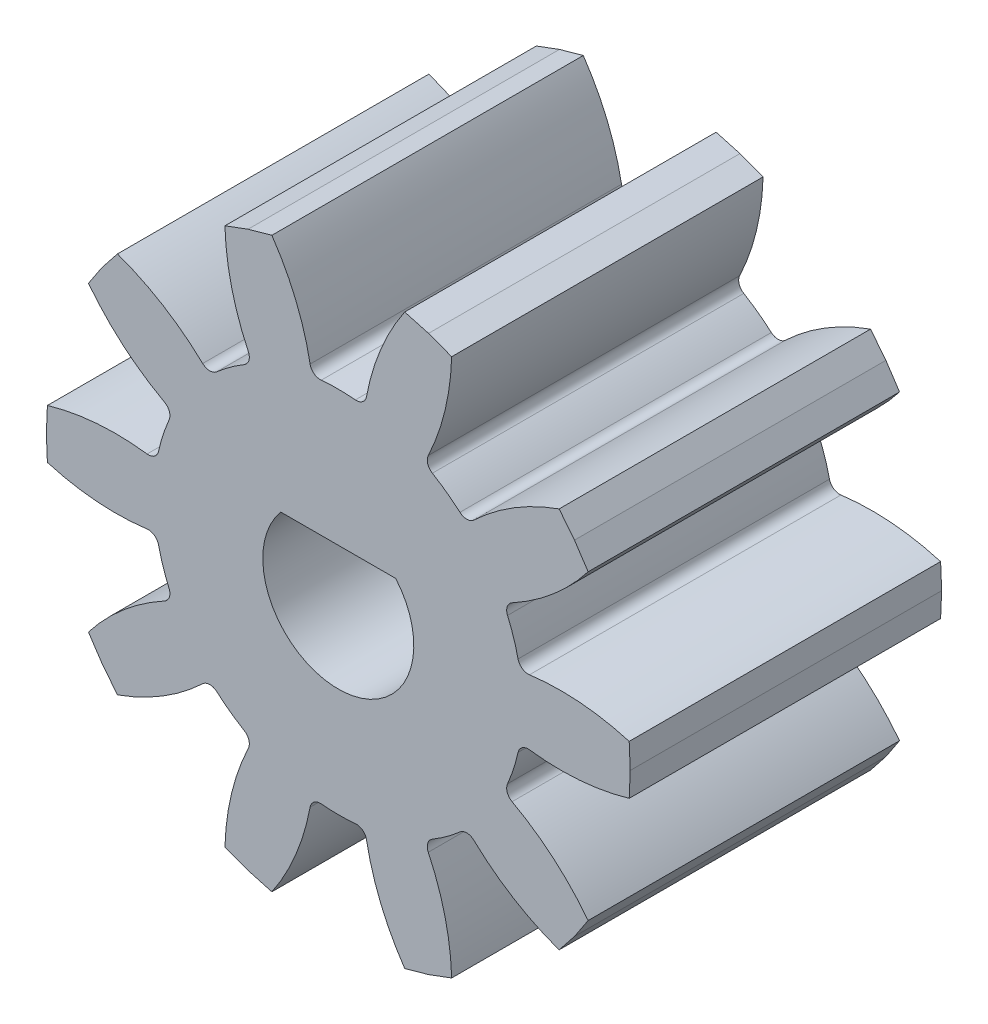
SolidWorks part; units mm, degrees
ref_plane "Front Plane" through (0, 0, 0) normal (0, 0, 1) x (1, 0, 0)
ref_plane "Top Plane" through (0, 0, 0) normal (0, 1, 0) x (1, 0, 0)
ref_plane "Right Plane" through (0, 0, 0) normal (1, 0, 0) x (0, 0, -1)
sketch "Sketch1" plane through (0, 0, 0) normal (0, 0, 1) x (1, 0, 0)
  line L0 (0, 0) -> (74.4139, 0) construction
  line L1 (0, 0) -> (5.6279, 1.8286) construction
  line L2 (0, 0) -> (74.4139, 12.7198) construction
  line L3 (0, 0) -> (74.4139, 6.3141) construction
  line L4 (9.3414, 0.7926) -> (9.375, 0)
  line L5 (0, 0) -> (5.6279, -1.8286) construction
  line L6 (0, 0) -> (5.6279, 1.8286)
  line L7 (0, 0) -> (5.6279, -1.8286) construction
  line L8 (0, 0) -> (5.6279, -1.8286)
  line L9 (9.3414, -0.7926) -> (9.375, 0)
  circle A0 centre (0, 0) radius 9.375 construction
  circle A1 centre (0, 0) radius 7.8125 construction
  circle A2 centre (0, 0) radius 5.9175 construction
  arc A3 (5.8329, 0.997) -> (9.3414, 0.7926) centre (7.1457, -6.6831) cw
  arc A4 (5.8329, 0.997) -> (5.6279, 1.8286) centre (0, 0) ccw
  arc A5 (5.8329, -0.997) -> (5.6279, -1.8286) centre (0, 0) cw
  arc A6 (5.8329, -0.997) -> (9.3414, -0.7926) centre (7.1457, 6.6831) ccw
  dimension "D1" = 18.75
  dimension "D2" = 1.5625
  dimension "D3" = 1.895
  dimension "D4" = 18
  dimension "D5" = 9.7
  dimension "D6" = 4.85
extrude "Boss-Extrude1" add sketch "Sketch1" along normal blind 10
fillet "Fillet1" radius 0.3325 2 edges at (5.8329, 0.997, 5) (5.8329, -0.997, 5)
pattern_circular "CirPattern1" count 10 over 360 about axis through (0, 0, 0) along (0, 0, 1) of "Boss-Extrude1", "Fillet1"
sketch "Sketch2" plane through (0, 0, 0) normal (0, 0, -1) x (-1, 0, 0)
  line L0 (-1.8439, 1.575) -> (1.8439, 1.575)
  arc A0 (-1.8439, 1.575) -> (1.8439, 1.575) centre (0, 0) ccw
  point P1 (0, -2.425)
  dimension "D1" = 4.85
  dimension "D2" = 4
extrude "Cut-Extrude1" cut sketch "Sketch2" against normal up to next
